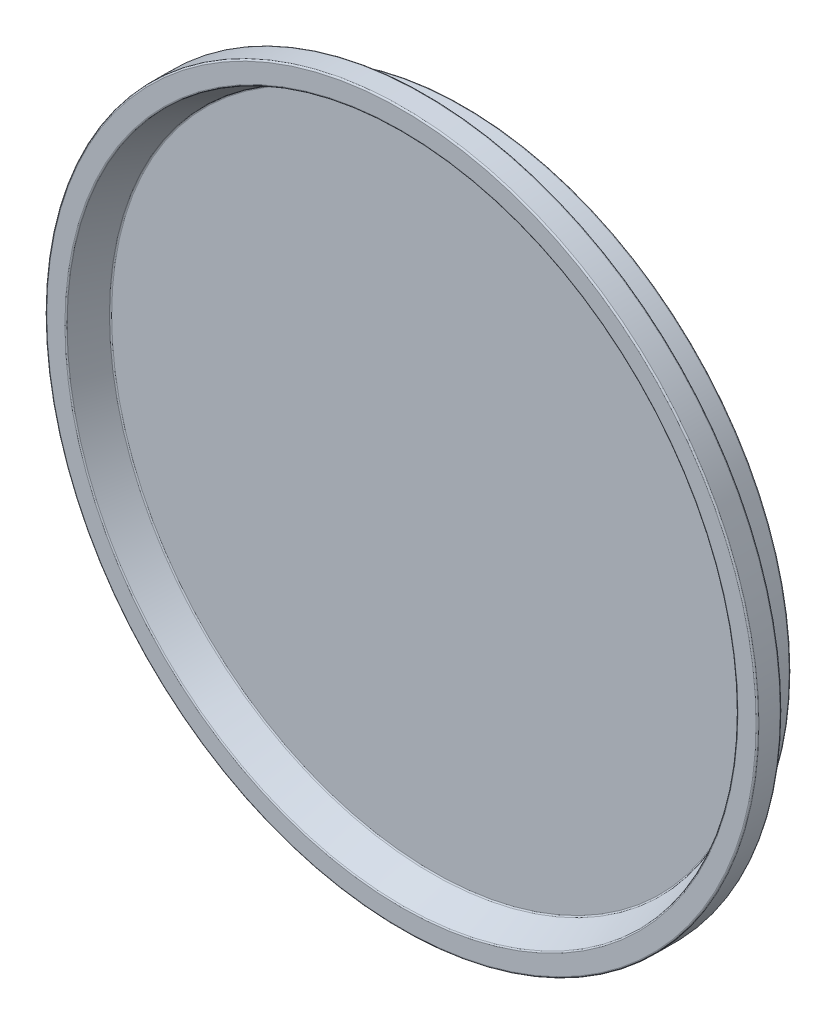
SolidWorks part; units mm, degrees
ref_plane "Front Plane" through (0, 0, 0) normal (1, 0, 0) x (0, 1, 0)
ref_plane "Top Plane" through (0, 0, 0) normal (0, 0, 1) x (0, 1, 0)
ref_plane "Right Plane" through (0, 0, 0) normal (0, 1, 0) x (-1, 0, 0)
sketch "Sketch1" plane through (0, 0, 0) normal (0, 1, 0) x (-1, 0, 0)
  line L0 (0, 0) -> (0, 2.2) construction
  line L1 (0, 2.2) -> (169.545, 2.2)
  line L2 (169.545, 2.2) -> (176.53, 18.796)
  line L3 (176.53, 18.796) -> (187.325, 18.796)
  line L4 (187.325, 18.796) -> (187.325, 6.096)
  line L5 (187.325, 6.096) -> (185.125, 6.096)
  line L6 (185.125, 6.096) -> (185.125, 16.596)
  line L7 (185.125, 16.596) -> (177.991, 16.596)
  line L8 (177.991, 16.596) -> (171.745, 1.7559)
  line L9 (171.745, 1.7559) -> (171.745, -14.224)
  line L10 (171.745, -14.224) -> (169.545, -14.224)
  line L11 (169.545, -14.224) -> (169.545, 0)
  line L12 (169.545, 0) -> (0, 0)
  line L13 (0, 0) -> (0, 2.2)
  line L14 (174.868, 9.1759) -> (172.8403, 10.0294) construction
  line L15 (181.558, 16.596) -> (181.558, 18.796) construction
  point P16 (185.125, 14.1535)
  point P19 (169.545, -22.4098)
  point P20 (179.4636, 16.596)
  dimension "D1" = 187.325
  dimension "D2" = 2.2
  dimension "D3" = 33.02
  dimension "D4" = 17.78
  dimension "D5" = 12.7
  dimension "D6" = 14.224
  dimension "D7" = 10.795
revolve "Revolve1" add sketch "Sketch1" angle 360 about L13
fillet "Fillet1" radius 0.762 11 edges at (-169.545, 0, 0) (-169.545, 0, -14.224) (-171.745, 0, -14.224) (-171.745, 0, 1.7559) (-177.991, 0, 16.596) (-185.125, 0, 16.596) (-185.125, 0, 6.096) (-187.325, 0, 6.096) (-176.53, 0, 18.796) (-169.545, 0, 2.2) (-187.325, 0, 18.796)
